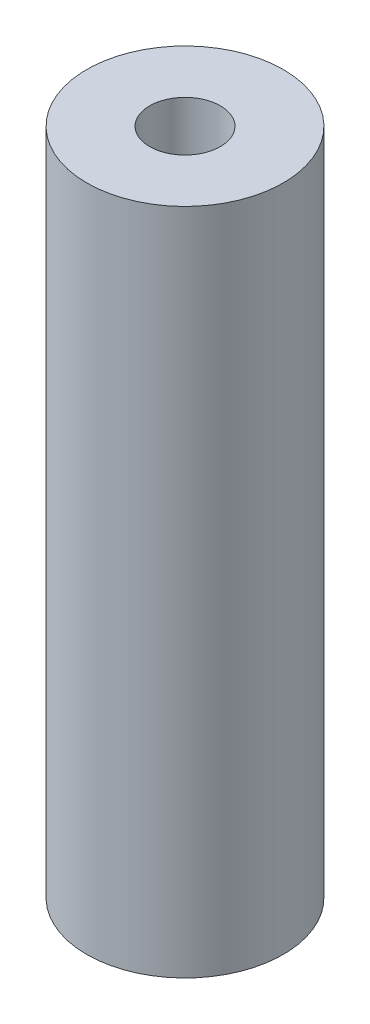
SolidWorks part; units mm, degrees
ref_plane "前视基准面" through (0, 0, 0) normal (0, 0, 1) x (1, 0, 0)
ref_plane "上视基准面" through (0, 0, 0) normal (0, 1, 0) x (1, 0, 0)
ref_plane "右视基准面" through (0, 0, 0) normal (1, 0, 0) x (0, 0, -1)
other "Configuration Table"
sketch "草图2" plane through (0, 0, 0) normal (0, 1, 0) x (1, 0, 0)
  circle A18 centre (0, 0) radius 2.5
  circle A19 centre (0, 0) radius 0.9
  point P3 (-6.3366, -4.4769)
  dimension "D1" = 1.8
  dimension "D2" = 5
extrude "凸台-拉伸1" add sketch "草图2" along normal blind 17
